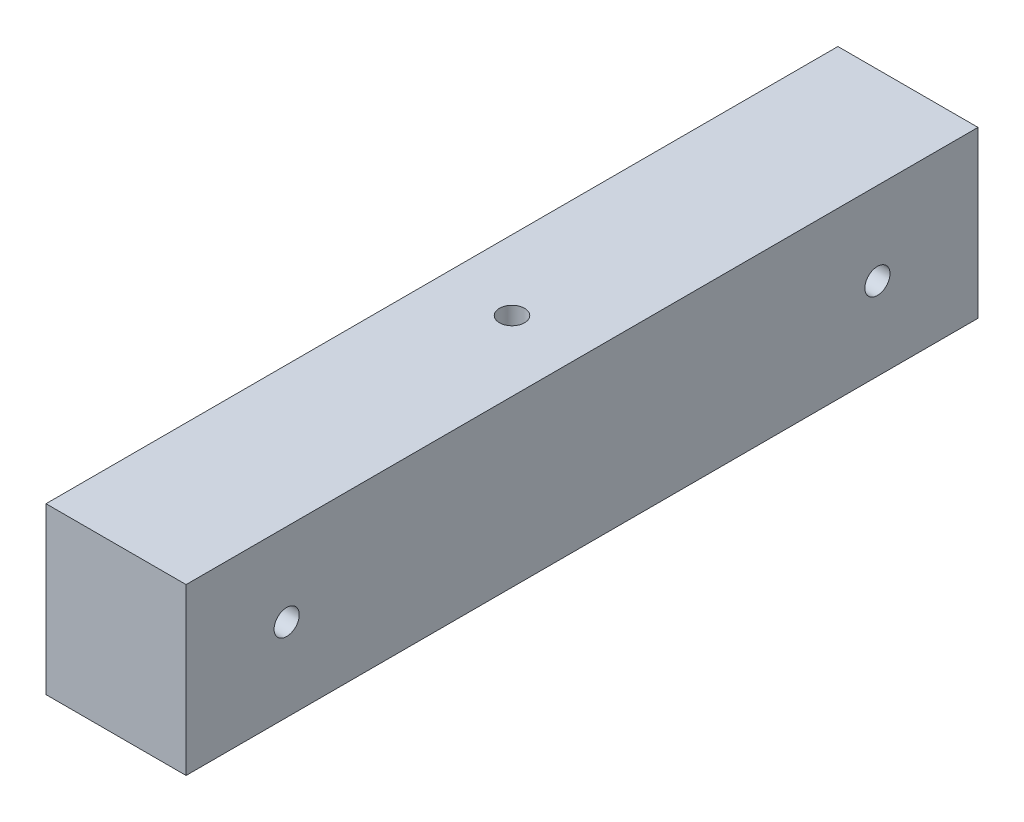
SolidWorks part; units mm, degrees
material "Pine"
ref_plane "Front Plane" through (0, 0, 0) normal (0, 0, 1) x (1, 0, 0)
ref_plane "Top Plane" through (0, 0, 0) normal (0, 1, 0) x (1, 0, 0)
ref_plane "Right Plane" through (0, 0, 0) normal (1, 0, 0) x (0, 0, -1)
sketch "Sketch1" plane through (0, 0, 0) normal (0, 0, 1) x (1, 0, 0)
  line L1 (0, 0) -> (17.69, 0)
  line L2 (0, 0) -> (0, 20.88)
  line L3 (0, 20.88) -> (17.69, 20.88)
  line L4 (17.69, 0) -> (17.69, 20.88)
  dimension "D1" = 17.69
  dimension "D2" = 20.88
extrude "Boss-Extrude1" add sketch "Sketch1" along normal blind 100
sketch "Sketch2" plane through (0, 20.88, 0) normal (0, 1, 0) x (1, 0, 0)
  line L0 (17.69, 0) -> (0, 0) construction
  line L1 (0, -100) -> (0, 0) construction
  circle A0 centre (8.845, -50) radius 1.5875
  point P0 (8.845, 0)
  point P1 (0, -50)
  point P4 (8.845, -50)
  dimension "D1" = 3.175
extrude "Cut-Extrude1" cut sketch "Sketch2" against normal blind 106.78
sketch "Sketch3" plane through (17.69, 0, 0) normal (1, 0, 0) x (0, 0, -1)
  line L0 (-100, 0) -> (-100, 20.88) construction
  line L1 (0, 0) -> (0, 20.88) construction
  line L2 (-100, 20.88) -> (0, 20.88) construction
  circle A0 centre (-87.3, 10.44) radius 1.5875
  circle A1 centre (-12.7, 10.44) radius 1.5875
  point P0 (-100, 20.88)
  point P1 (-100, 0)
  point P3 (-100, 10.44)
  point P5 (-87.3, 10.44)
  point P8 (-12.7, 10.44)
  point P9 (-48.4125, 20.88)
  point P10 (-48.4125, 0)
  dimension "D1" = 3.175
  dimension "D2" = 3.175
  dimension "D3" = 12.7
  dimension "D4" = 12.7
  dimension "D5" = 10.44
  dimension "D6" = 10.44
extrude "Cut-Extrude2" cut sketch "Sketch3" against normal blind 100
